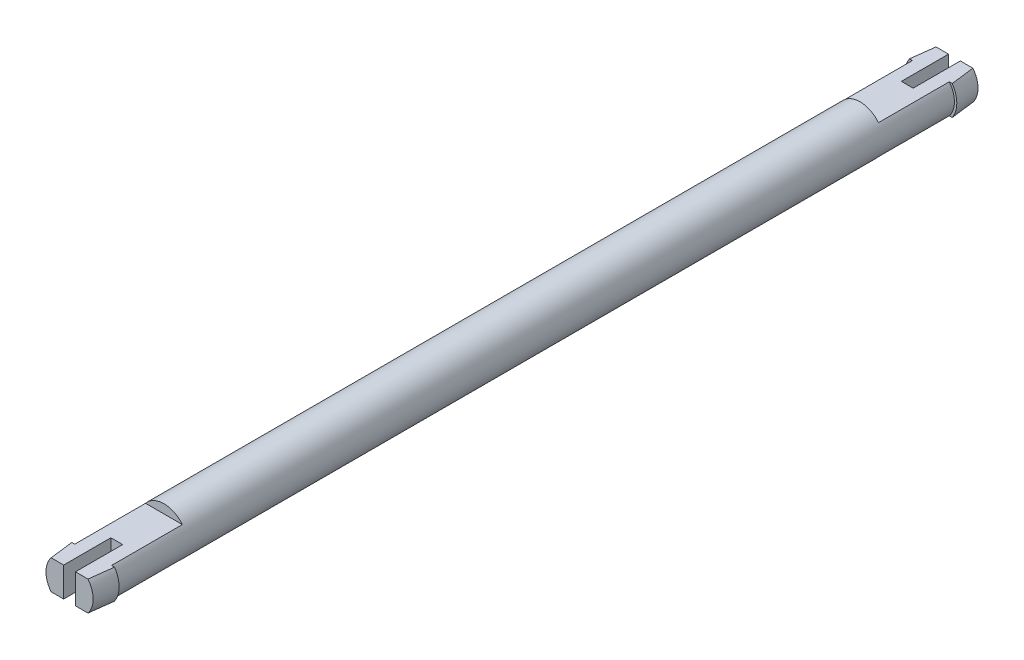
SolidWorks part; units mm, degrees
ref_plane "前视基准面" through (0, 0, 0) normal (0, 0, 1) x (1, 0, 0)
ref_plane "上视基准面" through (0, 0, 0) normal (0, 1, 0) x (1, 0, 0)
ref_plane "右视基准面" through (0, 0, 0) normal (1, 0, 0) x (0, 0, -1)
sketch "草图1" plane through (0, 0, 0) normal (0, 0, 1) x (1, 0, 0)
  circle A0 centre (0, 0) radius 2
extrude "凸台-拉伸1" add sketch "草图1" against normal blind 75
sketch "草图2" plane through (0, 0, 0) normal (0, 1, 0) x (1, 0, 0)
  line L0 (0, 0) -> (0, 2)
  line L1 (0, 2) -> (2.2, 2)
  line L2 (0, 0) -> (2, 0)
  line L3 (2, 0) -> (2.2, 2)
  dimension "D1" = 2.2
  dimension "D2" = 2
revolve "旋转1" add sketch "草图2" angle 360 about L0
sketch "草图3" plane through (0, 0, 0) normal (0, 0, 1) x (1, 0, 0)
  line L0 (-2.1, 1.25) -> (-2.1, 2.25)
  line L1 (-2.1, 1.25) -> (2.1, 1.25)
  line L2 (2.1, 1.25) -> (2.1, 2.25)
  line L3 (-2.1, -1.25) -> (2.1, -1.25)
  line L5 (-2.1, -2.25) -> (2.1, -2.25)
  line L6 (-2.1, -2.25) -> (-2.1, -1.25)
  line L7 (-2.1, 2.25) -> (2.1, 2.25)
  line L8 (2.1, -2.25) -> (2.1, -1.25)
  dimension "D1" = 1.25
  dimension "D2" = 1.25
  dimension "D3" = 1
  dimension "D4" = 1
extrude "切除-拉伸1" cut sketch "草图3" against normal blind 8
sketch "草图4" plane through (0, -1.25, 0) normal (0, -1, 0) x (1, 0, 0)
  line L0 (1.5612, 0) -> (-1.5612, 0) construction
  line L1 (-0.5, 0) -> (0.5, 0)
  line L2 (-0.5, 0) -> (-0.5, -4)
  line L3 (-0.5, -4) -> (0.5, -4)
  line L4 (0.5, 0) -> (0.5, -4)
extrude "切除-拉伸2" cut sketch "草图4" against normal up to next
sketch "草图5" plane through (0, 0, 0) normal (0, 1, 0) x (1, 0, 0)
  line L0 (0, 75) -> (0, 73)
  line L1 (2, 75) -> (-2, 75) construction
  line L2 (0, 73) -> (2.2, 73)
  line L3 (2.2, 73) -> (2, 75)
  line L4 (2, 75) -> (0, 75)
  line L5 (0, 58.1377) -> (0, 60.3241) construction
  dimension "D1" = 2.2
  dimension "D2" = 2
revolve "旋转2" add sketch "草图5" angle 360 about L5
sketch "草图6" plane through (0, 0, -75) normal (0, 0, -1) x (-1, 0, 0)
  line L1 (-2.1, 1.25) -> (2.1, 1.25)
  line L2 (-2.1, 1.25) -> (-2.1, 2.25)
  line L3 (-2.1, 2.25) -> (2.1, 2.25)
  line L4 (2.1, 1.25) -> (2.1, 2.25)
  line L5 (-2.1, -1.25) -> (2.1, -1.25)
  line L6 (-2.1, -1.25) -> (-2.1, -2.25)
  line L7 (-2.1, -2.25) -> (2.1, -2.25)
  line L8 (2.1, -1.25) -> (2.1, -2.25)
  dimension "D1" = 1.25
  dimension "D2" = 1.25
  dimension "D3" = 1
  dimension "D4" = 1
extrude "切除-拉伸3" cut sketch "草图6" against normal blind 8
sketch "草图7" plane through (0, 1.25, 0) normal (0, 1, 0) x (1, 0, 0)
  line L0 (0, 75) -> (0, 71) construction
  line L1 (-1.5612, 75) -> (1.5612, 75) construction
  line L2 (-0.5, 71) -> (0.5, 71)
  line L3 (0.5, 71) -> (0.5, 75)
  line L4 (0.5, 75) -> (-0.5, 75)
  line L5 (-0.5, 71) -> (-0.5, 75)
  dimension "D1" = 4
  dimension "D2" = 0.5
extrude "切除-拉伸4" cut sketch "草图7" against normal through all
